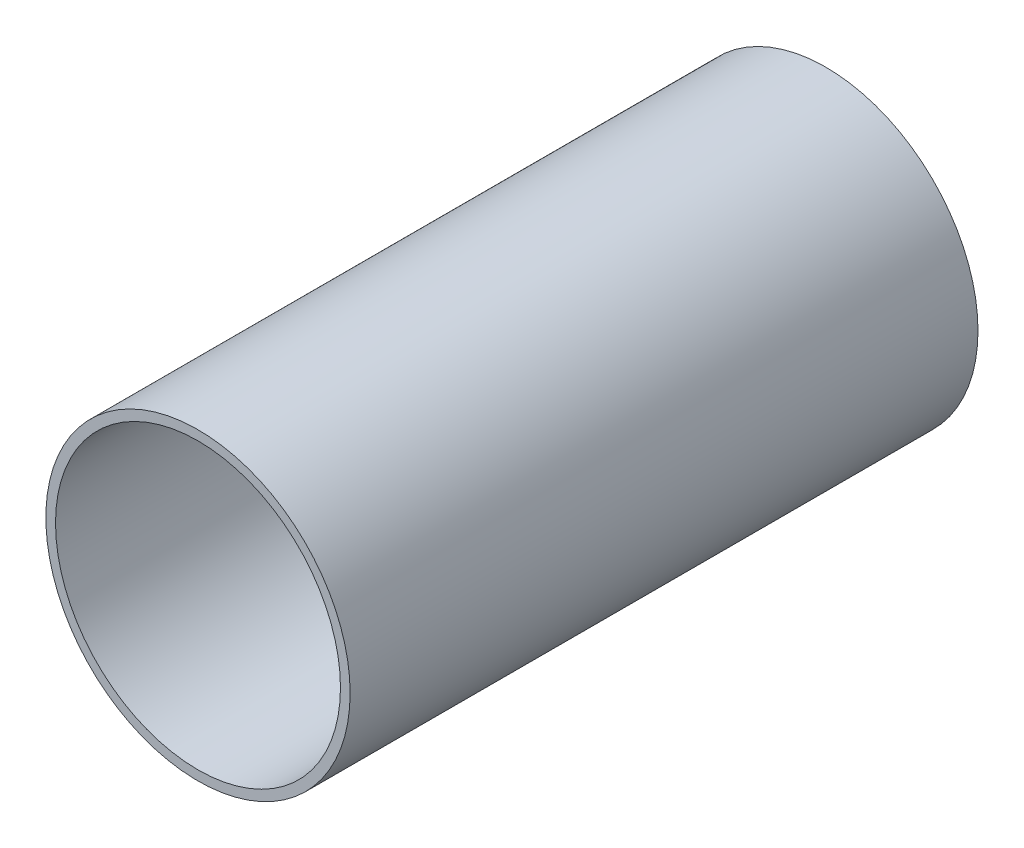
SolidWorks part; units mm, degrees
ref_plane "Plan de face" through (0, 0, 0) normal (0, 0, 1) x (1, 0, 0)
ref_plane "Plan de dessus" through (0, 0, 0) normal (0, 1, 0) x (1, 0, 0)
ref_plane "Plan de droite" through (0, 0, 0) normal (1, 0, 0) x (0, 0, -1)
sketch "Esquisse1" plane through (0, 0, 0) normal (0, 0, 1) x (1, 0, 0)
  circle A0 centre (0, 0) radius 31.5
  circle A1 centre (0, 0) radius 29.5
  dimension "D1" = 63
  dimension "D2" = 59
extrude "Boss.-Extru.1" add sketch "Esquisse1" along normal blind 130
